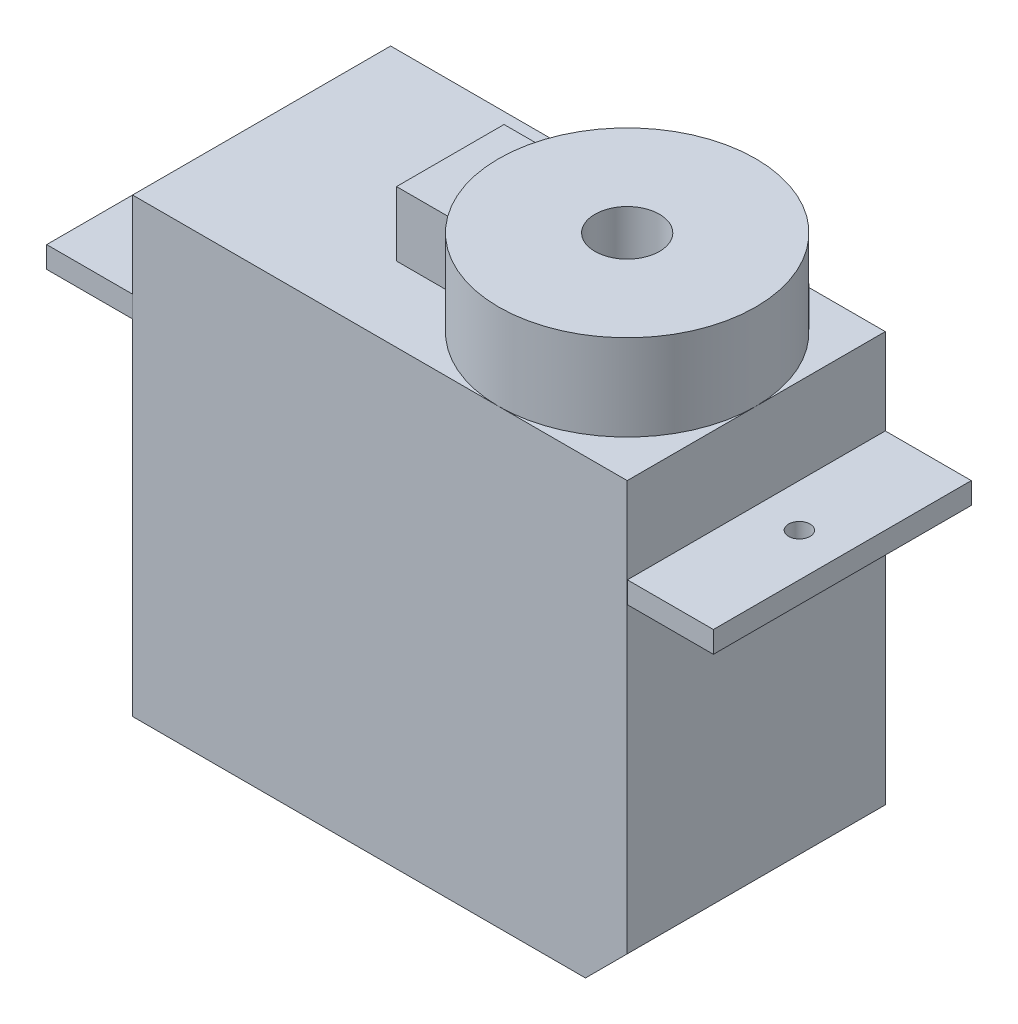
SolidWorks part; units mm, degrees
ref_plane "Plan de face" through (0, 0, 0) normal (0, 0, 1) x (1, 0, 0)
ref_plane "Plan de dessus" through (0, 0, 0) normal (0, 1, 0) x (1, 0, 0)
ref_plane "Plan de droite" through (0, 0, 0) normal (1, 0, 0) x (0, 0, -1)
sketch "Esquisse1" plane through (0, 0, 0) normal (0, 1, 0) x (1, 0, 0)
  line L1 (-11.5, 6) -> (11.5, 6)
  line L2 (-11.5, 6) -> (-11.5, -6)
  line L3 (-11.5, -6) -> (11.5, -6)
  line L4 (11.5, 6) -> (11.5, -6)
  line L5 (-11.5, 6) -> (11.5, -6) construction
  line L6 (-11.5, -6) -> (11.5, 6) construction
  point P0 (0, 0)
  dimension "D1" = 12
  dimension "D2" = 23
extrude "Boss.-Extru.1" add sketch "Esquisse1" along normal blind 21
ref_plane "Plan1" through (0, 16, 0) normal (0, 1, 0) x (1, 0, 0)
sketch "Esquisse2" plane through (0, 16, 0) normal (0, 1, 0) x (1, 0, 0)
  line L1 (11.5, 6) -> (15.5, 6)
  line L2 (11.5, 6) -> (11.5, -5.9926)
  line L3 (11.5, -5.9926) -> (15.5, -5.9926)
  line L4 (15.5, 6) -> (15.5, -5.9926)
  dimension "D1" = 4
extrude "Boss.-Extru.2" add sketch "Esquisse2" along normal blind 1
sketch "Esquisse3" plane through (0, 17, 0) normal (0, 1, 0) x (1, 0, 0)
  line L0 (11.5, 6) -> (15.5, -5.9926) construction
  line L1 (15.5, -5.9926) -> (11.5, -6) construction
  line L2 (11.5, -6) -> (15.5, 6) construction
  circle A0 centre (13.5, 0.0037) radius 0.5
  dimension "D1" = 1
extrude "Enlèv. mat.-Extru.1" cut sketch "Esquisse3" against normal blind 1
mirror "Symétrie1" about plane through (0, 0, 0) normal (1, 0, 0) of "Boss.-Extru.2"
mirror "Symétrie2" about plane through (0, 0, 0) normal (1, 0, 0) of "Enlèv. mat.-Extru.1"
sketch "Esquisse4" plane through (0, 21, 0) normal (0, 1, 0) x (1, 0, 0)
  circle A0 centre (5.5236, -0.0236) radius 5.9764
extrude "Boss.-Extru.3" add sketch "Esquisse4" along normal blind 4
sketch "Esquisse5" plane through (0, 21, 0) normal (0, 1, 0) x (1, 0, 0)
  line L1 (1.7971, 2.4764) -> (-2.7029, 2.4764)
  line L2 (1.7971, 2.4764) -> (1.7971, -2.5236)
  line L3 (1.7971, -2.5236) -> (-2.7029, -2.5236)
  line L4 (-2.7029, 2.4764) -> (-2.7029, -2.5236)
  line L5 (1.7971, 2.4764) -> (-2.7029, -2.5236) construction
  line L6 (1.7971, -2.5236) -> (-2.7029, 2.4764) construction
  arc A0 (11.5, -0.0236) -> (5.5236, -6) centre (5.5236, -0.0236) ccw construction
  circle A1 centre (5.5236, -0.0236) radius 5.9764 construction
  point P0 (-0.4529, -0.0236)
  dimension "D1" = 4.5
  dimension "D2" = 5
extrude "Boss.-Extru.4" add sketch "Esquisse5" along normal blind 3
sketch "Esquisse6" plane through (0, 0, 6) normal (0, 0, 1) x (1, 0, 0)
  line L0 (9.5594, 0) -> (11.5, 1.9406)
  line L1 (-11.5, 0) -> (11.5, 0) construction
  line L2 (11.5, 21) -> (11.5, 0) construction
  line L3 (9.5594, 0) -> (11.5, 0)
  line L4 (11.5, 0) -> (11.5, 1.9406)
extrude "Enlèv. mat.-Extru.3" cut sketch "Esquisse6" against normal through all
sketch "Esquisse7" plane through (0, 25, 0) normal (0, 1, 0) x (1, 0, 0)
  line L0 (-0.4529, -0.0236) -> (11.5, -0.0236) construction
  line L1 (11.5, -0.0236) -> (5.5236, 5.9529) construction
  line L2 (5.5236, 5.9529) -> (5.5236, -6) construction
  arc A0 (0.0952, 2.4764) -> (0.0952, -2.5236) centre (5.5236, -0.0236) ccw construction
  circle A1 centre (5.5236, -0.0236) radius 5.9764 construction
  arc A2 (11.5, -0.0236) -> (0.0952, 2.4764) centre (5.5236, -0.0236) ccw construction
  circle A3 centre (5.5236, -0.0236) radius 1.5
  dimension "D1" = 3
extrude "Enlèv. mat.-Extru.4" cut sketch "Esquisse7" against normal blind 3
